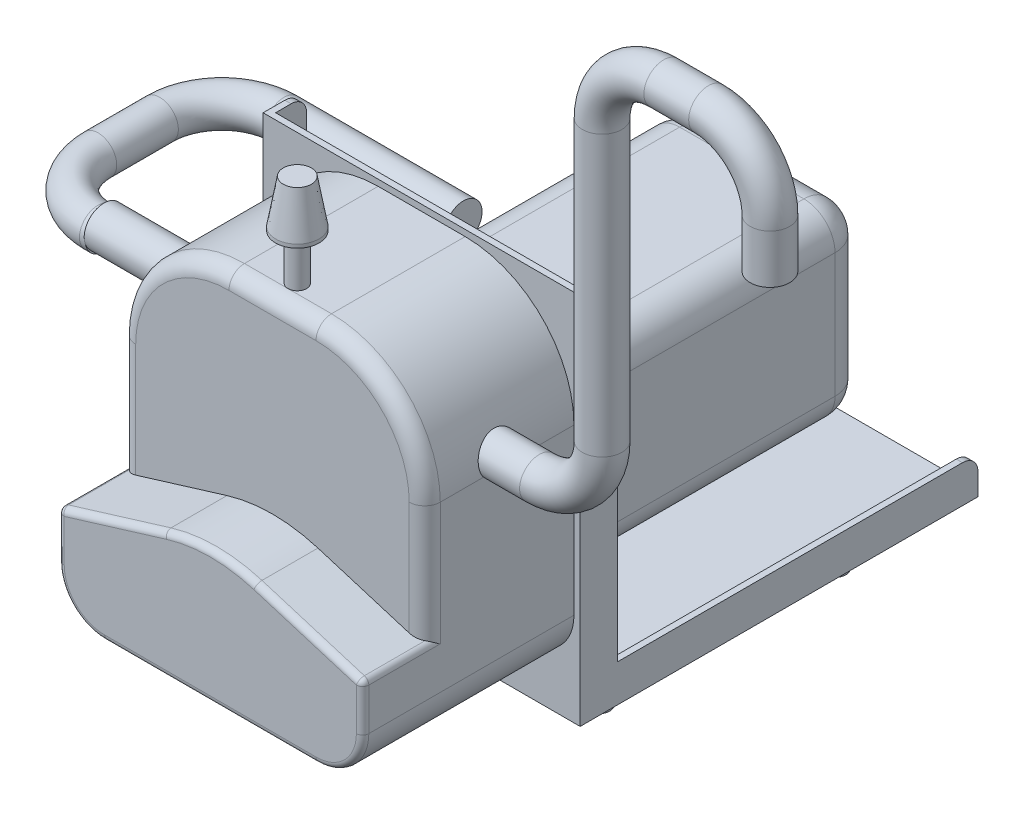
SolidWorks part; units mm, degrees
ref_plane "Front Plane" through (0, 0, 0) normal (0, 0, 1) x (1, 0, 0)
ref_plane "Top Plane" through (0, 0, 0) normal (0, 1, 0) x (1, 0, 0)
ref_plane "Right Plane" through (0, 0, 0) normal (1, 0, 0) x (0, 0, -1)
sketch "Sketch1" plane through (0, 0, 0) normal (0, 0, 1) x (1, 0, 0)
  line L1 (-51, -60) -> (51, -60)
  line L2 (-51, -60) -> (-51, 60)
  line L3 (-51, 60) -> (51, 60)
  line L4 (51, -60) -> (51, 60)
  line L5 (-51, -60) -> (51, 60) construction
  line L6 (-51, 60) -> (51, -60) construction
  point P0 (0, 0)
  dimension "D1" = 102
  dimension "D2" = 120
extrude "Boss-Extrude1" add sketch "Sketch1" along normal blind 2
sketch "Sketch2" plane through (0, -60, 0) normal (0, -1, 0) x (1, 0, 0)
  line L0 (51, 2) -> (51, 0) construction
  line L1 (-51, 2) -> (51, 2)
  line L2 (-51, 2) -> (-51, -126)
  line L3 (-51, -126) -> (51, -126)
  line L4 (51, 2) -> (51, -126)
  dimension "D1" = 128
extrude "Boss-Extrude2" add sketch "Sketch2" against normal blind 2
sketch "Sketch3" plane through (51, 0, 0) normal (1, 0, 0) x (0, 0, -1)
  line L1 (-2, 60) -> (10, 60)
  line L2 (-2, 60) -> (-2, -48)
  line L4 (10, 60) -> (10, -48)
  line L6 (126, -60) -> (-2, -60)
  line L7 (126, -60) -> (126, -48)
  line L8 (126, -48) -> (10, -48)
  line L9 (-2, -60) -> (-2, -48)
  dimension "D1" = 12
extrude "Boss-Extrude3" add sketch "Sketch3" against normal blind 2
mirror "Mirror1" about plane through (0, 0, 0) normal (1, 0, 0) of "Boss-Extrude3"
fillet "Fillet1" radius 5 4 edges at (-50, -48, -126) (50, -48, -126) (-50, 60, -10) (50, 60, -10)
sketch "Sketch5" plane through (0, -60, 0) normal (0, -1, 0) x (1, 0, 0)
  line L0 (-51, 2) -> (51, 2) construction
  line L1 (-42, -13) -> (42, -13) construction
  circle A0 centre (-42, -13) radius 3.5
  circle A1 centre (42, -13) radius 3.5
  circle A2 centre (-42, -89) radius 3.5
  circle A3 centre (42, -89) radius 3.5
  circle A4 centre (-42, -13) radius 2.5
  circle A5 centre (42, -13) radius 2.5
  circle A6 centre (42, -89) radius 2.5
  circle A7 centre (-42, -89) radius 2.5
  point P8 (0, -13)
  dimension "D2" = 7
  dimension "D5" = 5
  dimension "D1" = 76
  dimension "D3" = 15
  dimension "D4" = 84
extrude "Boss-Extrude4" add sketch "Sketch5" along normal offset from surface (6 mm away) 126 up to face at (0, 60, -2)
sketch "Sketch4" plane through (0, 0, 2) normal (0, 0, 1) x (1, 0, 0)
  line L0 (-51, 60) -> (-51, -60) construction
  line L1 (-49, -45) -> (49, -45)
  line L2 (-49, -45) -> (-49, 58)
  line L3 (-49, 58) -> (49, 58)
  line L4 (49, -45) -> (49, 58)
  line L5 (-49, -45) -> (49, 58) construction
  line L6 (-49, 58) -> (49, -45) construction
  line L7 (51, -60) -> (51, 60) construction
  line L8 (-45.5, -66) -> (-38.5, -66) construction
  line L9 (51, 60) -> (-51, 60) construction
  point P0 (0, 6.5)
  dimension "D1" = 2
  dimension "D2" = 2
  dimension "D3" = 21
  dimension "D4" = 2
extrude "Boss-Extrude5" add sketch "Sketch4" along normal offset from surface (68 mm away) 196 up to face at (0, -56, -126)
fillet "Fillet2" radius 35 2 edges at (-49, 58, 36) (49, 58, 36)
fillet "Fillet3" radius 15 2 edges at (49, -45, 36) (-49, -45, 36)
sketch "Sketch6" plane through (0, 0, 70) normal (0, 0, 1) x (1, 0, 0)
  line L0 (-49, -15) -> (-14.6357, -4.4803)
  line L1 (14.6357, -4.4803) -> (49, -15)
  line L4 (-34, -45) -> (34, -45)
  line L5 (49, -30) -> (49, 23)
  line L6 (14, 58) -> (-14, 58)
  line L7 (-49, 23) -> (-49, -30)
  line L9 (49, -15) -> (49, 23)
  line L10 (14, 58) -> (-14, 58)
  line L11 (-49, 23) -> (-49, -15)
  arc A0 (-14.6357, -4.4803) -> (14.6357, -4.4803) centre (0, -52.2903) cw
  arc A4 (34, -45) -> (49, -30) centre (34, -30) ccw
  arc A5 (49, 23) -> (14, 58) centre (14, 23) ccw
  arc A6 (-14, 58) -> (-49, 23) centre (-14, 23) ccw
  arc A7 (-49, -30) -> (-34, -45) centre (-34, -30) ccw
  arc A9 (49, 23) -> (14, 58) centre (14, 23) ccw
  arc A10 (-14, 58) -> (-49, 23) centre (-14, 23) ccw
  point P18 (0, 0)
  dimension "D3" = 50
  dimension "D2" = 73
  dimension "D1" = 0
extrude "Cut-Extrude1" cut sketch "Sketch6" against normal blind 20
fillet "Fillet4" radius 5 5 edges at (49, 4, 50) (38.7487, 47.7487, 50) (-49, 4, 50) (-38.7487, 47.7487, 50) (0, 58, 50)
fillet "Fillet5" radius 2 10 edges at (-31.8179, -9.7402, 70) (31.8179, -9.7402, 70) (-49, -15, 57.5) (49, -15, 57.5) (0, -2.2903, 70) (-49, -22.5, 70) (-44.6066, -40.6066, 70) (0, -45, 70) (44.6066, -40.6066, 70) (49, -22.5, 70)
sketch "Sketch8" plane through (0, 0, 0) normal (0, 0, -1) x (-1, 0, 0)
  line L0 (51, -60) -> (-51, -60) construction
  line L1 (-30, -40) -> (30, -40)
  line L2 (-30, -40) -> (-30, 20)
  line L3 (-30, 20) -> (30, 20)
  line L4 (30, -40) -> (30, 20)
  line L5 (-30, -40) -> (30, 20) construction
  line L6 (-30, 20) -> (30, -40) construction
  point P0 (0, -10)
  dimension "D1" = 60
  dimension "D2" = 60
  dimension "D3" = 50
extrude "Boss-Extrude6" add sketch "Sketch8" along normal offset from surface (111 mm away) 15 up to face at (0, -56, -126)
fillet "Fillet6" radius 10 8 edges at (30, -10, -111) (0, 20, -111) (-30, -10, -111) (0, -40, -111) (-30, -40, -55.5) (-30, 20, -55.5) (30, -40, -55.5) (30, 20, -55.5)
sketch "Sketch10" plane through (0, 58, 0) normal (0, 1, 0) x (1, 0, 0)
  line L0 (51, -2) -> (-51, -2) construction
  circle A0 centre (0, -42) radius 3
  dimension "D1" = 6
  dimension "D2" = 40
extrude "Boss-Extrude7" add sketch "Sketch10" along normal blind 29.85
sketch "Sketch11" plane through (0, 87.85, 0) normal (0, 1, 0) x (1, 0, 0)
  circle A0 centre (0, -42) radius 7
  dimension "D1" = 14
extrude "Boss-Extrude8" add sketch "Sketch11" against normal blind 15.15
chamfer "Chamfer1" distance 14 angle 10 1 edges at (0, 87.85, 49)
sketch "Sketch15" plane through (0, 0, 2) normal (0, 0, 1) x (1, 0, 0)
  line L5 (14.6357, -4.4803) -> (44, -13.4694)
  line L6 (44, -13.4694) -> (44, 23)
  line L7 (14, 53) -> (-14, 53)
  line L8 (-44, 23) -> (-44, -13.4694)
  line L9 (-44, -13.4694) -> (-14.6357, -4.4803)
  line L11 (44, -13.4694) -> (44, 23)
  line L12 (14, 53) -> (-14, 53)
  line L13 (-44, 23) -> (-44, -13.4694)
  line L15 (-44, -16.4794) -> (-44, -13.4694)
  line L16 (34, -40) -> (-34, -40)
  line L17 (-44, -30) -> (-44, -16.4794)
  line L18 (34, -40) -> (-34, -40)
  line L19 (-44, -30) -> (-44, -16.4794)
  line L20 (44, -30) -> (44, -16.4794)
  line L21 (44, -30) -> (44, -16.4794)
  line L22 (44, -16.4794) -> (44, -13.4694)
  arc A3 (44, 23) -> (14, 53) centre (14, 23) ccw
  arc A4 (-14, 53) -> (-44, 23) centre (-14, 23) ccw
  arc A5 (14.6357, -4.4803) -> (-14.6357, -4.4803) centre (0, -52.2903) ccw
  arc A6 (44, 23) -> (14, 53) centre (14, 23) ccw
  arc A7 (-14, 53) -> (-44, 23) centre (-14, 23) ccw
  arc A9 (-44, -30) -> (-34, -40) centre (-34, -30) ccw
  arc A10 (-44, -30) -> (-34, -40) centre (-34, -30) ccw
  arc A13 (34, -40) -> (44, -30) centre (34, -30) ccw
  arc A14 (34, -40) -> (44, -30) centre (34, -30) ccw
  dimension "D1" = 0
  dimension "D2" = 5
  dimension "D3" = 5
extrude "Cut-Extrude2" cut sketch "Sketch15" along normal offset from surface (38 mm away) 10 up to face at (0, 16.3396, 50)
sketch "Sketch12" plane through (-49, 0, 0) normal (-1, 0, 0) x (0, 0, 1)
  circle A0 centre (26.1706, 27.0446) radius 6.35
  circle A1 centre (26.1706, 27.0446) radius 5.08
  dimension "D1" = 12.7
  dimension "D2" = 10.16
sketch "Sketch13" plane through (0, 0, 50) normal (0, 0, 1) x (1, 0, 0)
  line L0 (82.0301, 47.244) -> (82.0301, 137.2021)
  line L1 (102.0301, 157.2021) -> (116.4356, 157.2021)
  line L2 (136.4356, 137.2021) -> (136.4356, 121.5189)
  line L4 (-78.0594, 27.244) -> (62.0301, 27.244)
  arc A1 (62.0301, 27.244) -> (82.0301, 47.244) centre (62.0301, 47.244) ccw
  arc A2 (136.4356, 137.2021) -> (116.4356, 157.2021) centre (116.4356, 137.2021) ccw
  arc A3 (82.0301, 137.2021) -> (102.0301, 157.2021) centre (102.0301, 137.2021) cw
  dimension "D2" = 20
sweep "Sweep1" add profiles "Sketch12" path "Sketch13"
scale "Scale1" scale about centroid uniform scaling yes scale factor 0.5
ref_plane "Plane1" through (0, 0, 0) normal (-1, 0, 0) x (0, 0, 1)
ref_plane "Plane2" through (0, 9, 0) normal (0, 1, 0) x (1, 0, 0)
sketch "Sketch16" plane through (0, 9, 0) normal (0, 1, 0) x (1, 0, 0)
  line L0 (-38.3989, -3.8578) -> (-39.3347, -3.8578)
  line L1 (-38.3989, -0.6828) -> (-38.3989, -7.0328) construction
  line L2 (-49.4061, 6.2136) -> (-49.4061, 16.1276)
  line L3 (-39.4061, 26.1276) -> (-10.5487, 26.1276)
  arc A0 (-49.4061, 16.1276) -> (-39.4061, 26.1276) centre (-39.4061, 16.1276) cw
  arc A1 (-39.3347, -3.8578) -> (-49.4061, 6.2136) centre (-39.3347, 6.2136) cw
  dimension "D1" = 10
sweep "Sweep3" add path "Sketch16" circular profile diameter 6 parameters "D3"=6
